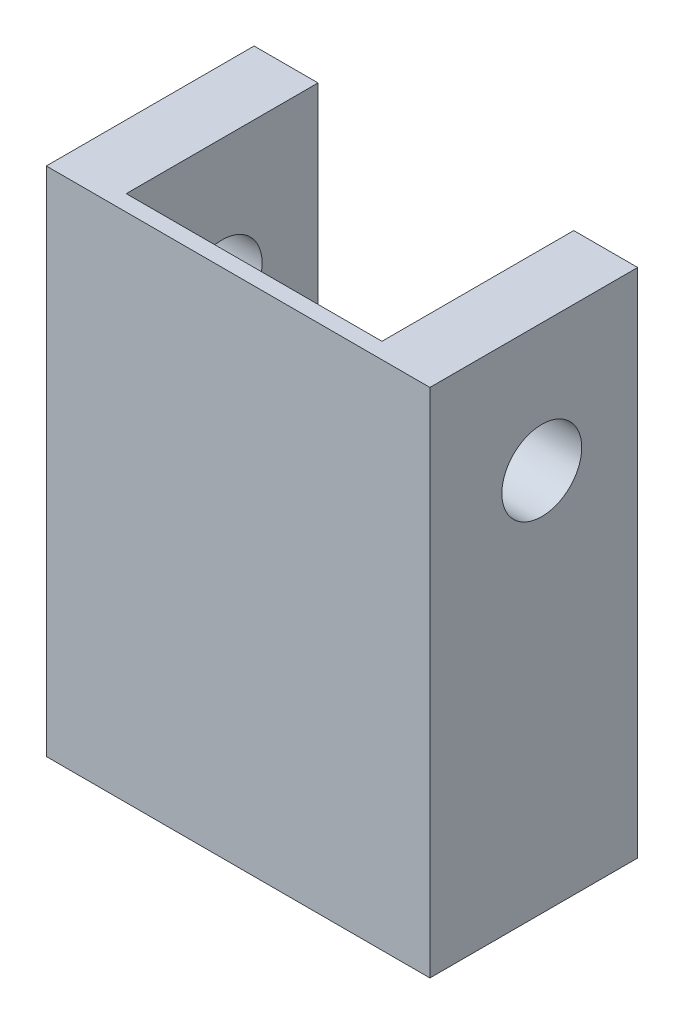
SolidWorks part; units mm, degrees
ref_plane "Front Plane" through (0, 0, 0) normal (0, 0, 1) x (1, 0, 0)
ref_plane "Top Plane" through (0, 0, 0) normal (0, 1, 0) x (1, 0, 0)
ref_plane "Right Plane" through (0, 0, 0) normal (1, 0, 0) x (0, 0, -1)
sketch "Sketch1" plane through (0, 0, 0) normal (0, 0, 1) x (1, 0, 0)
  line L0 (-38.1, 0) -> (38.1, 0)
  line L1 (38.1, 0) -> (38.1, 101.6)
  line L2 (38.1, 101.6) -> (25.4, 101.6)
  line L3 (25.4, 101.6) -> (25.4, 50.8)
  line L4 (25.4, 50.8) -> (-25.4, 50.8)
  line L5 (0, 50.8) -> (0, 0) construction
  line L6 (-25.4, 101.6) -> (-25.4, 50.8)
  line L7 (-38.1, 101.6) -> (-25.4, 101.6)
  line L8 (-38.1, 0) -> (-38.1, 101.6)
  dimension "D1" = 50.8
  dimension "D2" = 50.8
  dimension "D3" = 12.7
  dimension "D4" = 50.8
extrude "Boss-Extrude1" add sketch "Sketch1" along normal mid plane 38.1
sketch "Sketch2" plane through (0, 0, 0) normal (1, 0, 0) x (0, 0, -1)
  line L0 (-19.05, 101.6) -> (19.05, 101.6) construction
  circle A0 centre (0, 76.2) radius 7.9375
  dimension "D1" = 15.875
  dimension "D2" = 25.4
extrude "Cut-Extrude1" cut sketch "Sketch2" against normal through all both and the other way through all
sketch "Sketch3" plane through (0, 0, 19.05) normal (0, 0, 1) x (1, 0, 0)
  line L1 (-38.1, 101.6) -> (38.1, 101.6)
  line L2 (-38.1, 101.6) -> (-38.1, 0)
  line L3 (-38.1, 0) -> (38.1, 0)
  line L4 (38.1, 101.6) -> (38.1, 0)
extrude "Boss-Extrude2" add sketch "Sketch3" along normal blind 3.175
